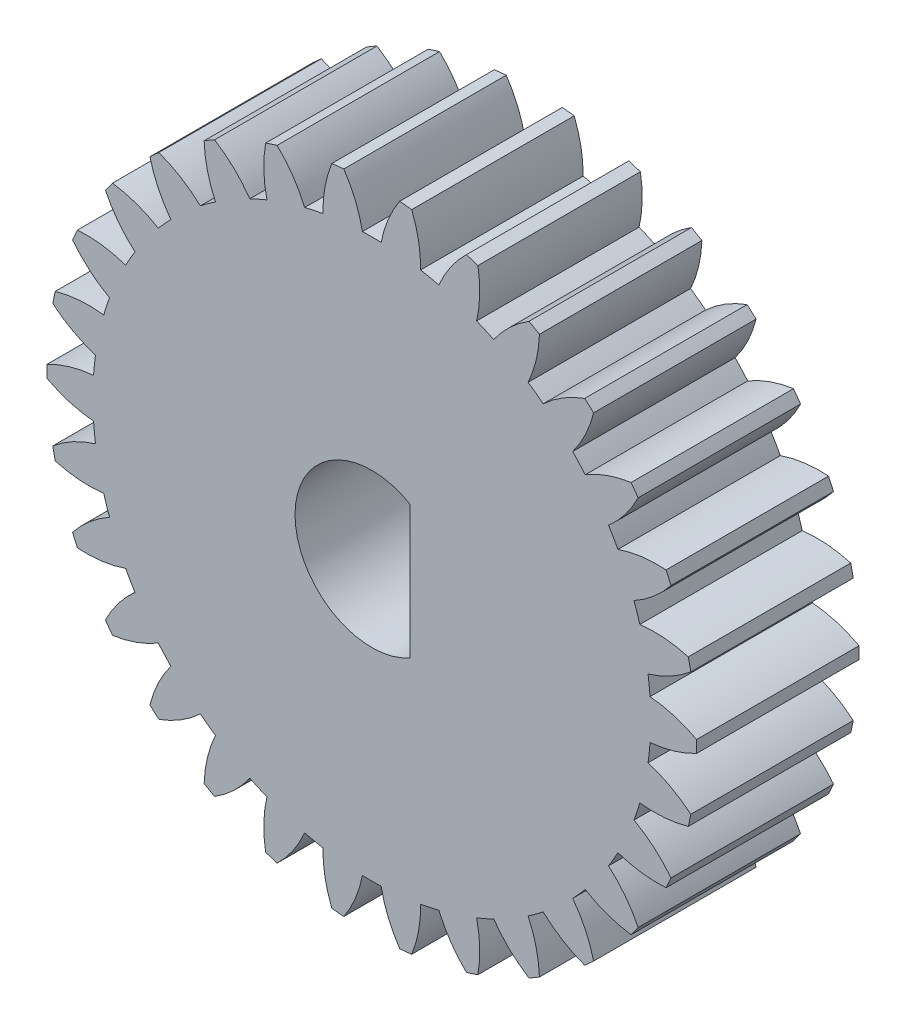
SolidWorks part; units mm, degrees
ref_plane "Front Plane" through (0, 0, 0) normal (0, 0, 1) x (1, 0, 0)
ref_plane "Top Plane" through (0, 0, 0) normal (0, 1, 0) x (1, 0, 0)
ref_plane "Right Plane" through (0, 0, 0) normal (1, 0, 0) x (0, 0, -1)
sketch "Sketch1" plane through (0, 0, 0) normal (0, 0, 1) x (1, 0, 0)
  line L0 (1.5, 2.5981) -> (1.5, -2.5981)
  arc A0 (1.5, 2.5981) -> (1.5, -2.5981) centre (0, 0) ccw
  arc B0 (-12.6978, -0.2355) -> (-10.8753, -0.7756) centre (-10.4606, 3.9688) ccw
  arc B1 (-10.8753, -0.7756) -> (-10.7989, -1.5025) centre (0, 0) ccw
  arc B2 (-10.7989, -1.5025) -> (-12.4693, -2.4097) centre (-9.4069, -6.057) ccw
  arc B3 (-12.4693, -2.4097) -> (-12.3714, -2.8704) centre (0, 0) ccw
  arc B4 (-12.3714, -2.8704) -> (-10.4764, -3.0197) centre (-11.0572, 1.7072) ccw
  arc B5 (-10.4764, -3.0197) -> (-10.2506, -3.7149) centre (0, 0) ccw
  arc B6 (-10.2506, -3.7149) -> (-11.6958, -4.9495) centre (-7.942, -7.8804) ccw
  arc B7 (-11.6958, -4.9495) -> (-11.5042, -5.3798) centre (0, 0) ccw
  arc B8 (-11.5042, -5.3798) -> (-9.6197, -5.1319) centre (-11.1705, -0.629) ccw
  arc B9 (-9.6197, -5.1319) -> (-9.2542, -5.7649) centre (0, 0) ccw
  arc B10 (-9.2542, -5.7649) -> (-10.4112, -7.2731) centre (-6.13, -9.3594) ccw
  arc B11 (-10.4112, -7.2731) -> (-10.1343, -7.6541) centre (0, 0) ccw
  arc B12 (-10.1343, -7.6541) -> (-8.3425, -7.0198) centre (-10.7956, -2.9377) ccw
  arc B13 (-8.3425, -7.0198) -> (-7.8534, -7.563) centre (0, 0) ccw
  arc B14 (-7.8534, -7.563) -> (-8.6715, -9.2787) centre (-4.0501, -10.4294) ccw
  arc B15 (-8.6715, -9.2787) -> (-8.3215, -9.5939) centre (0, 0) ccw
  arc B16 (-8.3215, -9.5939) -> (-6.7006, -8.6009) centre (-9.9489, -5.1181) ccw
  arc B17 (-6.7006, -8.6009) -> (-6.1093, -9.0305) centre (0, 0) ccw
  arc B18 (-6.1093, -9.0305) -> (-6.5529, -10.8789) centre (-1.7932, -11.0436) ccw
  arc B19 (-6.5529, -10.8789) -> (-6.145, -11.1144) centre (0, 0) ccw
  arc B20 (-6.145, -11.1144) -> (-4.766, -9.8061) centre (-8.6674, -7.0747) ccw
  arc B21 (-4.766, -9.8061) -> (-4.0983, -10.1034) centre (0, 0) ccw
  arc B22 (-4.0983, -10.1034) -> (-4.1478, -12.0036) centre (0.5421, -11.1751) ccw
  arc B23 (-4.1478, -12.0036) -> (-3.6999, -12.1491) centre (0, 0) ccw
  arc B24 (-3.6999, -12.1491) -> (-2.623, -10.5827) centre (-7.0071, -8.7222) ccw
  arc B25 (-2.623, -10.5827) -> (-1.9081, -10.7347) centre (0, 0) ccw
  arc B26 (-1.9081, -10.7347) -> (-1.5615, -12.6036) centre (2.8537, -10.8182) ccw
  arc B27 (-1.5615, -12.6036) -> (-1.0931, -12.6529) centre (0, 0) ccw
  arc B28 (-1.0931, -12.6529) -> (-0.3654, -10.8968) centre (-5.0405, -9.9885) ccw
  arc B29 (-0.3654, -10.8968) -> (0.3654, -10.8968) centre (0, 0) ccw
  arc B30 (0.3654, -10.8968) -> (1.0931, -12.6529) centre (5.0405, -9.9885) ccw
  arc B31 (1.0931, -12.6529) -> (1.5615, -12.6036) centre (0, 0) ccw
  arc B32 (1.5615, -12.6036) -> (1.9081, -10.7347) centre (-2.8537, -10.8182) ccw
  arc B33 (1.9081, -10.7347) -> (2.623, -10.5827) centre (0, 0) ccw
  arc B34 (2.623, -10.5827) -> (3.6999, -12.1491) centre (7.0071, -8.7222) ccw
  arc B35 (3.6999, -12.1491) -> (4.1478, -12.0036) centre (0, 0) ccw
  arc B36 (4.1478, -12.0036) -> (4.0983, -10.1034) centre (-0.5421, -11.1751) ccw
  arc B37 (4.0983, -10.1034) -> (4.766, -9.8061) centre (0, 0) ccw
  arc B38 (4.766, -9.8061) -> (6.145, -11.1144) centre (8.6674, -7.0747) ccw
  arc B39 (6.145, -11.1144) -> (6.5529, -10.8789) centre (0, 0) ccw
  arc B40 (6.5529, -10.8789) -> (6.1093, -9.0305) centre (1.7932, -11.0436) ccw
  arc B41 (6.1093, -9.0305) -> (6.7006, -8.6009) centre (0, 0) ccw
  arc B42 (6.7006, -8.6009) -> (8.3215, -9.5939) centre (9.9489, -5.1181) ccw
  arc B43 (8.3215, -9.5939) -> (8.6715, -9.2787) centre (0, 0) ccw
  arc B44 (8.6715, -9.2787) -> (7.8534, -7.563) centre (4.0501, -10.4294) ccw
  arc B45 (7.8534, -7.563) -> (8.3425, -7.0198) centre (0, 0) ccw
  arc B46 (8.3425, -7.0198) -> (10.1343, -7.6541) centre (10.7956, -2.9377) ccw
  arc B47 (10.1343, -7.6541) -> (10.4112, -7.2731) centre (0, 0) ccw
  arc B48 (10.4112, -7.2731) -> (9.2542, -5.7649) centre (6.13, -9.3594) ccw
  arc B49 (9.2542, -5.7649) -> (9.6197, -5.1319) centre (0, 0) ccw
  arc B50 (9.6197, -5.1319) -> (11.5042, -5.3798) centre (11.1705, -0.629) ccw
  arc B51 (11.5042, -5.3798) -> (11.6958, -4.9495) centre (0, 0) ccw
  arc B52 (11.6958, -4.9495) -> (10.2506, -3.7149) centre (7.942, -7.8804) ccw
  arc B53 (10.2506, -3.7149) -> (10.4764, -3.0197) centre (0, 0) ccw
  arc B54 (10.4764, -3.0197) -> (12.3714, -2.8704) centre (11.0572, 1.7072) ccw
  arc B55 (12.3714, -2.8704) -> (12.4693, -2.4097) centre (0, 0) ccw
  arc B56 (12.4693, -2.4097) -> (10.7989, -1.5025) centre (9.4069, -6.057) ccw
  arc B57 (10.7989, -1.5025) -> (10.8753, -0.7756) centre (0, 0) ccw
  arc B58 (10.8753, -0.7756) -> (12.6978, -0.2355) centre (10.4606, 3.9688) ccw
  arc B59 (12.6978, -0.2355) -> (12.6978, 0.2355) centre (0, 0) ccw
  arc B60 (12.6978, 0.2355) -> (10.8753, 0.7756) centre (10.4606, -3.9688) ccw
  arc B61 (10.8753, 0.7756) -> (10.7989, 1.5025) centre (0, 0) ccw
  arc B62 (10.7989, 1.5025) -> (12.4693, 2.4097) centre (9.4069, 6.057) ccw
  arc B63 (12.4693, 2.4097) -> (12.3714, 2.8704) centre (0, 0) ccw
  arc B64 (12.3714, 2.8704) -> (10.4764, 3.0197) centre (11.0572, -1.7072) ccw
  arc B65 (10.4764, 3.0197) -> (10.2506, 3.7149) centre (0, 0) ccw
  arc B66 (10.2506, 3.7149) -> (11.6958, 4.9495) centre (7.942, 7.8804) ccw
  arc B67 (11.6958, 4.9495) -> (11.5042, 5.3798) centre (0, 0) ccw
  arc B68 (11.5042, 5.3798) -> (9.6197, 5.1319) centre (11.1705, 0.629) ccw
  arc B69 (9.6197, 5.1319) -> (9.2542, 5.7649) centre (0, 0) ccw
  arc B70 (9.2542, 5.7649) -> (10.4112, 7.2731) centre (6.13, 9.3594) ccw
  arc B71 (10.4112, 7.2731) -> (10.1343, 7.6541) centre (0, 0) ccw
  arc B72 (10.1343, 7.6541) -> (8.3425, 7.0198) centre (10.7956, 2.9377) ccw
  arc B73 (8.3425, 7.0198) -> (7.8534, 7.563) centre (0, 0) ccw
  arc B74 (7.8534, 7.563) -> (8.6715, 9.2787) centre (4.0501, 10.4294) ccw
  arc B75 (8.6715, 9.2787) -> (8.3215, 9.5939) centre (0, 0) ccw
  arc B76 (8.3215, 9.5939) -> (6.7006, 8.6009) centre (9.9489, 5.1181) ccw
  arc B77 (6.7006, 8.6009) -> (6.1093, 9.0305) centre (0, 0) ccw
  arc B78 (6.1093, 9.0305) -> (6.5529, 10.8789) centre (1.7932, 11.0436) ccw
  arc B79 (6.5529, 10.8789) -> (6.145, 11.1144) centre (0, 0) ccw
  arc B80 (6.145, 11.1144) -> (4.766, 9.8061) centre (8.6674, 7.0747) ccw
  arc B81 (4.766, 9.8061) -> (4.0983, 10.1034) centre (0, 0) ccw
  arc B82 (4.0983, 10.1034) -> (4.1478, 12.0036) centre (-0.5421, 11.1751) ccw
  arc B83 (4.1478, 12.0036) -> (3.6999, 12.1491) centre (0, 0) ccw
  arc B84 (3.6999, 12.1491) -> (2.623, 10.5827) centre (7.0071, 8.7222) ccw
  arc B85 (2.623, 10.5827) -> (1.9081, 10.7347) centre (0, 0) ccw
  arc B86 (1.9081, 10.7347) -> (1.5615, 12.6036) centre (-2.8537, 10.8182) ccw
  arc B87 (1.5615, 12.6036) -> (1.0931, 12.6529) centre (0, 0) ccw
  arc B88 (1.0931, 12.6529) -> (0.3654, 10.8968) centre (5.0405, 9.9885) ccw
  arc B89 (0.3654, 10.8968) -> (-0.3654, 10.8968) centre (0, 0) ccw
  arc B90 (-0.3654, 10.8968) -> (-1.0931, 12.6529) centre (-5.0405, 9.9885) ccw
  arc B91 (-1.0931, 12.6529) -> (-1.5615, 12.6036) centre (0, 0) ccw
  arc B92 (-1.5615, 12.6036) -> (-1.9081, 10.7347) centre (2.8537, 10.8182) ccw
  arc B93 (-1.9081, 10.7347) -> (-2.623, 10.5827) centre (0, 0) ccw
  arc B94 (-2.623, 10.5827) -> (-3.6999, 12.1491) centre (-7.0071, 8.7222) ccw
  arc B95 (-3.6999, 12.1491) -> (-4.1478, 12.0036) centre (0, 0) ccw
  arc B96 (-4.1478, 12.0036) -> (-4.0983, 10.1034) centre (0.5421, 11.1751) ccw
  arc B97 (-4.0983, 10.1034) -> (-4.766, 9.8061) centre (0, 0) ccw
  arc B98 (-4.766, 9.8061) -> (-6.145, 11.1144) centre (-8.6674, 7.0747) ccw
  arc B99 (-6.145, 11.1144) -> (-6.5529, 10.8789) centre (0, 0) ccw
  arc B100 (-6.5529, 10.8789) -> (-6.1093, 9.0305) centre (-1.7932, 11.0436) ccw
  arc B101 (-6.1093, 9.0305) -> (-6.7006, 8.6009) centre (0, 0) ccw
  arc B102 (-6.7006, 8.6009) -> (-8.3215, 9.5939) centre (-9.9489, 5.1181) ccw
  arc B103 (-8.3215, 9.5939) -> (-8.6715, 9.2787) centre (0, 0) ccw
  arc B104 (-8.6715, 9.2787) -> (-7.8534, 7.563) centre (-4.0501, 10.4294) ccw
  arc B105 (-7.8534, 7.563) -> (-8.3425, 7.0198) centre (0, 0) ccw
  arc B106 (-8.3425, 7.0198) -> (-10.1343, 7.6541) centre (-10.7956, 2.9377) ccw
  arc B107 (-10.1343, 7.6541) -> (-10.4112, 7.2731) centre (0, 0) ccw
  arc B108 (-10.4112, 7.2731) -> (-9.2542, 5.7649) centre (-6.13, 9.3594) ccw
  arc B109 (-9.2542, 5.7649) -> (-9.6197, 5.1319) centre (0, 0) ccw
  arc B110 (-9.6197, 5.1319) -> (-11.5042, 5.3798) centre (-11.1705, 0.629) ccw
  arc B111 (-11.5042, 5.3798) -> (-11.6958, 4.9495) centre (0, 0) ccw
  arc B112 (-11.6958, 4.9495) -> (-10.2506, 3.7149) centre (-7.942, 7.8804) ccw
  arc B113 (-10.2506, 3.7149) -> (-10.4764, 3.0197) centre (0, 0) ccw
  arc B114 (-10.4764, 3.0197) -> (-12.3714, 2.8704) centre (-11.0572, -1.7072) ccw
  arc B115 (-12.3714, 2.8704) -> (-12.4693, 2.4097) centre (0, 0) ccw
  arc B116 (-12.4693, 2.4097) -> (-10.7989, 1.5025) centre (-9.4069, 6.057) ccw
  arc B117 (-10.7989, 1.5025) -> (-10.8753, 0.7756) centre (0, 0) ccw
  arc B118 (-10.8753, 0.7756) -> (-12.6978, 0.2355) centre (-10.4606, -3.9688) ccw
  arc B119 (-12.6978, 0.2355) -> (-12.6978, -0.2355) centre (0, 0) ccw
  dimension "D1" = 6
  dimension "D2" = 1.5
sketch_block_instance "Drive_Gear-1"
sketch_block "Drive_Gear"
extrude "Boss-Extrude1" add sketch "Sketch1" along normal blind 6.35
